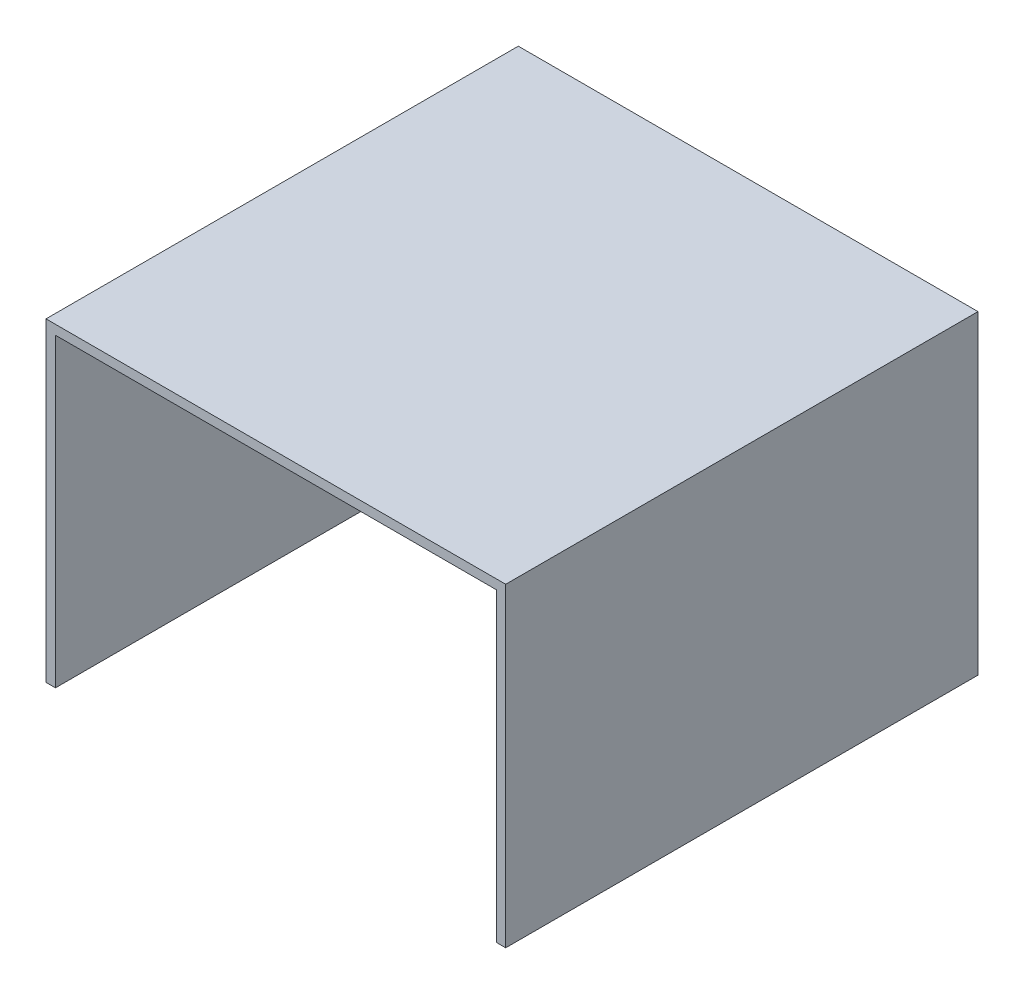
SolidWorks part; units mm, degrees
ref_plane "前视基准面" through (0, 0, 0) normal (0, 0, 1) x (1, 0, 0)
ref_plane "上视基准面" through (0, 0, 0) normal (0, 1, 0) x (1, 0, 0)
ref_plane "右视基准面" through (0, 0, 0) normal (1, 0, 0) x (0, 0, -1)
sketch "草图1" plane through (0, 0, 0) normal (0, 0, 1) x (1, 0, 0)
  line L0 (36.5, 25) -> (-36.5, 25)
  line L2 (35, -23.5) -> (35, 23.5)
  line L3 (35, 23.5) -> (-35, 23.5)
  line L4 (-35, -23.5) -> (-35, 23.5)
  line L7 (-36.5, -25) -> (-36.5, 25)
  line L8 (36.5, -25) -> (35, -25)
  line L9 (36.5, -25) -> (36.5, 25)
  line L10 (-35, -23.5) -> (-35, -25)
  line L11 (35, -23.5) -> (35, -25)
  line L12 (-35, -25) -> (-36.5, -25)
  line L13 (36.5, -25) -> (-36.5, -25) construction
  line L14 (35, -23.5) -> (-35, -23.5) construction
  point P0 (0, 0)
  dimension "D1" = 47
  dimension "D2" = 70
  dimension "D3" = 1.5
extrude "凸台-拉伸2" add sketch "草图1" along normal blind 75
